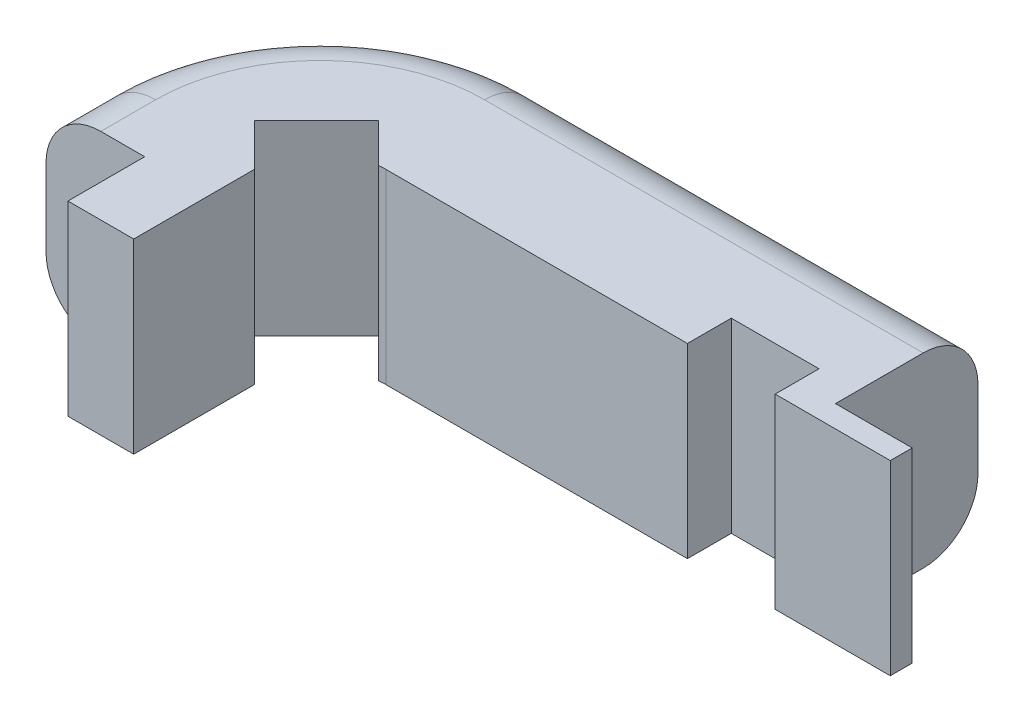
SolidWorks part; units mm, degrees
ref_plane "Alzado" through (0, 0, 0) normal (0, 0, 1) x (1, 0, 0)
ref_plane "Planta" through (0, 0, 0) normal (0, 1, 0) x (1, 0, 0)
ref_plane "Vista lateral" through (0, 0, 0) normal (1, 0, 0) x (0, 0, -1)
sketch "Croquis1" plane through (0, 0, 0) normal (0, 1, 0) x (1, 0, 0)
  line L1 (0, 0) -> (-40, 0)
  line L2 (0, 0) -> (0, -25)
  line L3 (0, -25) -> (-60, -25)
  line L4 (-60, -20) -> (-60, -25)
  arc A0 (-40, 0) -> (-60, -20) centre (-40, -20) ccw
  point P7 (-60, 0)
  dimension "D3" = 20
  dimension "D1" = 25
  dimension "D2" = 60
extrude "Saliente-Extruir1" add sketch "Croquis1" along normal blind 17
sketch "Croquis8" plane through (0, 0, 0) normal (1, 0, 0) x (0, 0, -1)
  line L0 (-5, 0) -> (0, 0)
  line L13 (0, 0) -> (0, 5)
  line L14 (0, 12) -> (0, 17)
  line L15 (0, 17) -> (-5, 17)
  arc A2 (0, 12) -> (-5, 17) centre (-5, 12) ccw
  arc A3 (-5, 0) -> (0, 5) centre (-5, 5) ccw
  point P9 (0, 17)
  point P10 (0, 0)
  dimension "D1" = 5
extrude "Cortar-Extruir3" cut sketch "Croquis8" against normal blind 40
sketch "Croquis12" plane through (0, 17, 0) normal (0, 1, 0) x (1, 0, 0)
  line L0 (0, -15) -> (-39, -15)
  line L1 (-45, -21) -> (-45, -25)
  line L3 (-45, -25) -> (0, -25)
  line L4 (0, -25) -> (0, -15)
  arc A0 (-39, -15) -> (-45, -21) centre (-39, -21) ccw
  dimension "D1" = 45
  dimension "D3" = 6
  dimension "D2" = 10
sketch "Croquis13" plane through (-40, 0, 0) normal (1, 0, 0) x (0, 0, -1)
  line L0 (-5, 17) -> (0, 17)
  line L1 (0, 17) -> (-20, 17) construction
  line L2 (0, 17) -> (0, 12)
  line L3 (0, 5) -> (0, 0)
  line L4 (0, 0) -> (-5, 0)
  line L5 (-20, 22.1208) -> (-20, -9.7768) construction
  line L6 (-20, 17) -> (-20, 0) construction
  arc A0 (0, 12) -> (-5, 17) centre (-5, 12) ccw
  arc A1 (-5, 0) -> (0, 5) centre (-5, 5) ccw
  arc A2 (0, 12) -> (-5, 17) centre (-5, 12) ccw construction
  arc A3 (-5, 0) -> (0, 5) centre (-5, 5) ccw construction
revolve "Cortar-Revolución1" cut sketch "Croquis13" angle 90 about L5
sketch "Croquis14" plane through (0, 0, 20) normal (0, 0, -1) x (-1, 0, 0)
  line L0 (60, 12) -> (40, 12) construction
  line L1 (55, 17) -> (60, 17)
  line L2 (60, 17) -> (60, 12)
  line L3 (60, 5) -> (60, 0)
  line L4 (60, 0) -> (55, 0)
  arc A0 (60, 12) -> (55, 17) centre (55, 12) ccw
  arc A1 (55, 0) -> (60, 5) centre (55, 5) ccw
  arc A2 (60, 12) -> (55, 17) centre (55, 12) ccw construction
  arc A3 (55, 0) -> (60, 5) centre (55, 5) ccw construction
extrude "Cortar-Extruir4" cut sketch "Croquis14" against normal blind 10
extrude "Cortar-Extruir5" cut sketch "Croquis12" against normal blind 27
sketch "Croquis15" plane through (0, 0, 25) normal (0, 0, 1) x (1, 0, 0)
  line L0 (-55, 0) -> (-45, 0) construction
  line L1 (-45, 17) -> (-51, 17)
  line L2 (-45, 17) -> (-45, 0)
  line L3 (-45, 0) -> (-51, 0)
  line L4 (-51, 17) -> (-51, 0)
  dimension "D1" = 6
extrude "Saliente-Extruir2" add sketch "Croquis15" along normal blind 7
sketch "Croquis16" plane through (0, 0, 0) normal (1, 0, 0) x (0, 0, -1)
  line L0 (-15, 0) -> (-5, 0) construction
  line L1 (-15, 17) -> (-13, 17)
  line L2 (-15, 17) -> (-15, 0)
  line L3 (-15, 0) -> (-13, 0)
  line L4 (-13, 17) -> (-13, 0)
  dimension "D1" = 2
extrude "Saliente-Extruir3" add sketch "Croquis16" along normal blind 7
sketch "Croquis17" plane through (0, 0, 0) normal (0, -1, 0) x (1, 0, 0)
  line L1 (-11.5, 15) -> (-3.5, 15)
  line L2 (-11.5, 15) -> (-11.5, 11)
  line L3 (-11.5, 11) -> (-3.5, 11)
  line L4 (-3.5, 15) -> (-3.5, 11)
  line L5 (-45, 21) -> (-48.8433, 17.1567)
  line L6 (-48.8433, 17.1567) -> (-43.1864, 11.4999)
  line L7 (-43.1864, 11.4999) -> (-39.6509, 15.0354)
  line L8 (-55, 25) -> (-51, 25) construction
  line L9 (0, 13) -> (0, 5) construction
  line L10 (7, 15) -> (-39, 15) construction
  arc A0 (-45, 21) -> (-39, 15) centre (-39, 21) ccw construction
  arc A1 (-45, 21) -> (-39.6509, 15.0354) centre (-39, 21) ccw
  dimension "D1" = 45
  dimension "D2" = 8
  dimension "D3" = 8
  dimension "D4" = 4
  dimension "D5" = 5
  dimension "D6" = 4
  dimension "D7" = 3.5
extrude "Cortar-Extruir6" cut sketch "Croquis17" against normal blind 23
